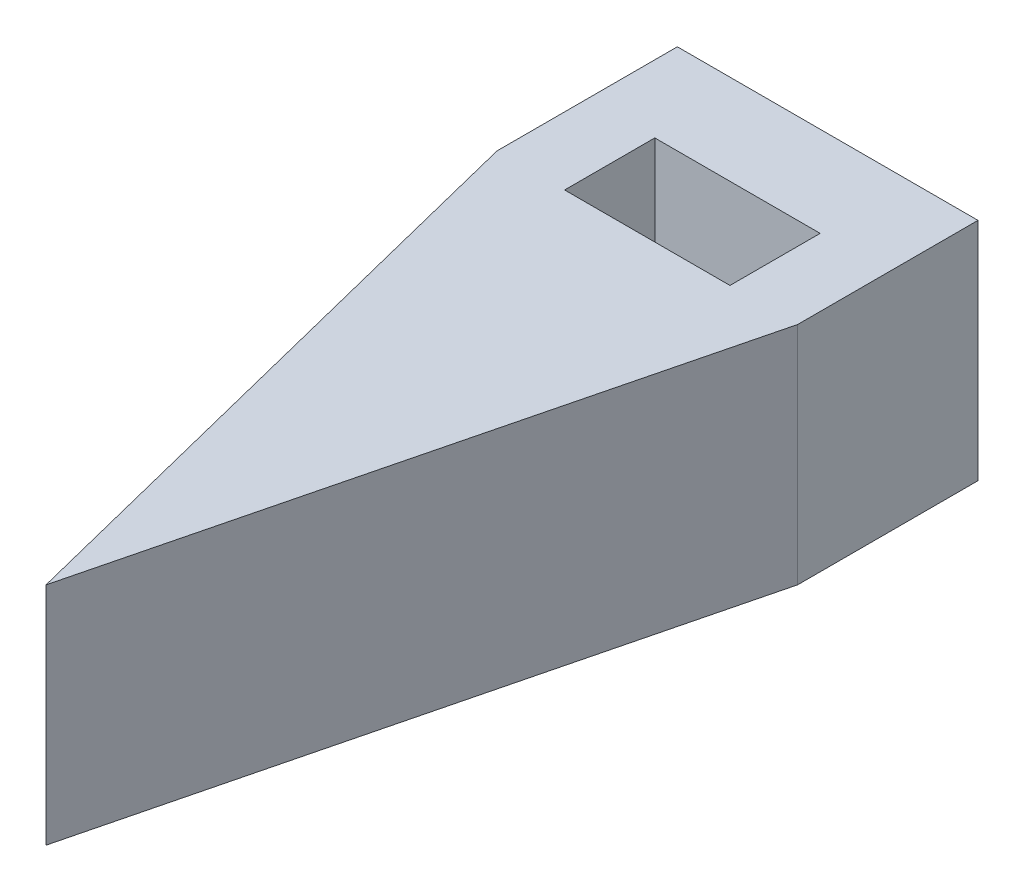
SolidWorks part; units mm, degrees
ref_plane "Front Plane" through (0, 0, 0) normal (0, 0, 1) x (1, 0, 0)
ref_plane "Top Plane" through (0, 0, 0) normal (0, 1, 0) x (1, 0, 0)
ref_plane "Right Plane" through (0, 0, 0) normal (1, 0, 0) x (0, 0, -1)
sketch "Sketch2" plane through (0, 0, 0) normal (0, 1, 0) x (1, 0, 0)
  line L7 (-5, -6) -> (0, -26)
  line L13 (0, 0) -> (0, -26) construction
  line L17 (-5, 0) -> (5, 0)
  line L23 (5, -6) -> (0, -26)
  line L27 (-2.75, -3) -> (2.75, -3)
  line L28 (-2.75, -3) -> (-2.75, -6)
  line L29 (-2.75, -6) -> (2.75, -6)
  line L30 (2.75, -3) -> (2.75, -6)
  line L34 (-5, 0) -> (-5, -6)
  line L35 (5, 0) -> (5, -6)
  point P4 (0, 0)
  point P10 (0, -6)
  dimension "D1" = 3
  dimension "D2" = 10
  dimension "D3" = 3
  dimension "D4" = 5.5
  dimension "D5" = 10
  dimension "D6" = 20
extrude "Body" add sketch "Sketch2" along normal mid plane 7.5
